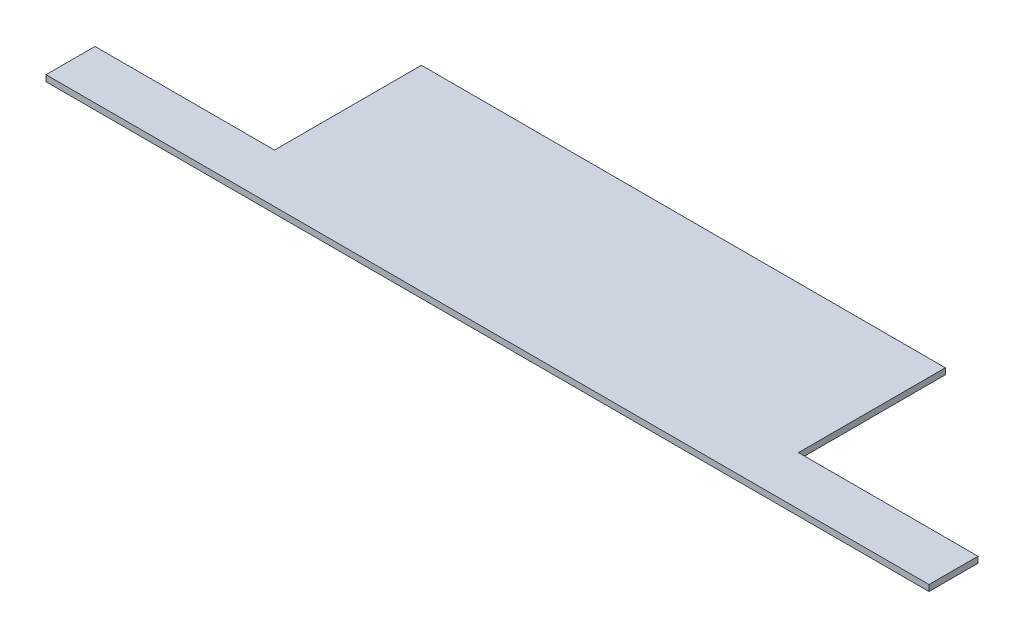
SolidWorks part; units mm, degrees
ref_plane "Front Plane" through (0, 0, 0) normal (0, 0, 1) x (1, 0, 0)
ref_plane "Top Plane" through (0, 0, 0) normal (0, 1, 0) x (1, 0, 0)
ref_plane "Right Plane" through (0, 0, 0) normal (1, 0, 0) x (0, 0, -1)
sketch "Sketch1" plane through (0, 0, 0) normal (0, 1, 0) x (1, 0, 0)
  line L1 (342.8997, -38.4034) -> (-344.2115, -38.4034)
  line L2 (342.8997, -38.4034) -> (342.8997, -0.3034)
  line L3 (203.1997, 113.9966) -> (-204.5115, 113.9966)
  line L4 (-344.2115, -38.4034) -> (-344.2115, -0.3034)
  line L9 (-344.2115, -0.3034) -> (-204.5115, -0.3034)
  line L10 (-204.5115, 113.9966) -> (-204.5115, -0.3034)
  line L13 (342.8997, -0.3034) -> (203.1997, -0.3034)
  line L14 (203.1997, 113.9966) -> (203.1997, -0.3034)
  point P0 (0, 0)
  dimension "D1" = 152.4
  dimension "D3" = 114.3
  dimension "D4" = 139.7
extrude "Boss-Extrude1" add sketch "Sketch1" along normal blind 4.7625
